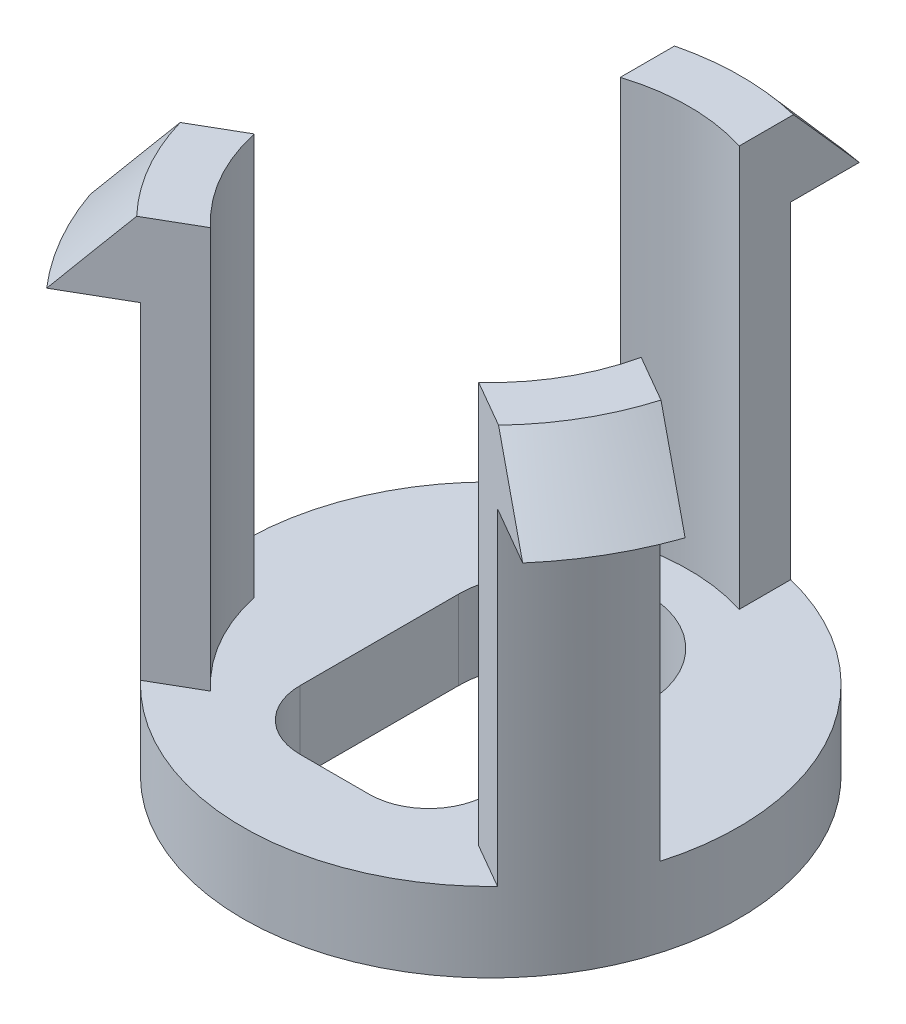
SolidWorks part; units mm, degrees
ref_plane "Front Plane" through (0, 0, 0) normal (0, 0, 1) x (1, 0, 0)
ref_plane "Top Plane" through (0, 0, 0) normal (0, 1, 0) x (1, 0, 0)
ref_plane "Right Plane" through (0, 0, 0) normal (1, 0, 0) x (0, 0, -1)
sketch "Sketch1" plane through (0, 0, 0) normal (0, 1, 0) x (1, 0, 0)
  circle A0 centre (0, 0) radius 5
  circle A1 centre (0, 0) radius 3.8 construction
  dimension "D1" = 10
  dimension "D2" = 1.2
extrude "Boss-Extrude1" add sketch "Sketch1" along normal blind 1.6
sketch "Sketch2" plane through (0, 1.6, 0) normal (0, 1, 0) x (1, 0, 0)
  line L2 (-1.2, 4.8539) -> (-1.2, 3.8158)
  line L4 (1.2, 4.8539) -> (1.2, 3.8158)
  circle A0 centre (0, 0) radius 5 construction
  arc A1 (1.2, 4.8539) -> (-1.2, 4.8539) centre (0, 0) ccw
  arc A2 (1.2, 3.8158) -> (-1.2, 3.8158) centre (0, 0) ccw
  circle A3 centre (0, 0) radius 5 construction
  circle A4 centre (0, 0) radius 4 construction
  dimension "D2" = 1.2
  dimension "D3" = 1.2
  dimension "D1" = 1
extrude "Boss-Extrude2" add sketch "Sketch2" along normal blind 8.1
pattern_circular "CirPattern3" count 3 over 360 about axis through (0, 0, 0) along (0, 1, 0) of "Boss-Extrude2"
sketch "Sketch3" plane through (0, 0, 0) normal (1, 0, 0) x (0, 0, -1)
  line L0 (5.0539, 9.7) -> (6.3539, 8.2)
  line L2 (6.3539, 8.2) -> (4.8539, 8.2)
  line L4 (4.8539, 9.7) -> (4.8539, 1.6) construction
  line L5 (4.8539, 8.2) -> (4.8539, 9.7)
  line L6 (4.8539, 9.7) -> (5.0539, 9.7)
  dimension "D1" = 1.5
  dimension "D2" = 1.5
  dimension "D3" = 0.2
sketch "Sketch6" plane through (0, 9.7, 0) normal (0, 1, 0) x (1, 0, 0)
  circle A0 centre (0, 0) radius 5
sweep "Sweep3" add profiles "Sketch3" path "Sketch6"
sketch "Sketch7" plane through (0, 1.6, 0) normal (0, 1, 0) x (1, 0, 0)
  line L0 (-3.9045, -0.8686) -> (-4.8036, -1.3877) construction
  line L1 (-3.9045, -0.8686) -> (-4.8036, -1.3877)
  line L2 (-1.2, 4.8539) -> (-1.2, 3.8158) construction
  line L3 (1.2, 3.8158) -> (1.2, 4.8539) construction
  line L4 (4.8036, -1.3877) -> (3.9045, -0.8686) construction
  line L5 (2.7045, -2.9471) -> (3.6036, -3.4662) construction
  line L6 (-3.6036, -3.4662) -> (-2.7045, -2.9471) construction
  line L7 (-1.2, 4.8539) -> (-1.2, 3.8158)
  line L8 (1.2, 3.8158) -> (1.2, 4.8539)
  line L9 (4.8036, -1.3877) -> (3.9045, -0.8686)
  line L10 (2.7045, -2.9471) -> (3.6036, -3.4662)
  line L11 (-3.6036, -3.4662) -> (-2.7045, -2.9471)
  arc A0 (-1.2, 4.8539) -> (-4.8036, -1.3877) centre (0, 0) ccw construction
  arc A1 (-1.2, 4.8539) -> (-4.8036, -1.3877) centre (0, 0) ccw
  arc A2 (4.8036, -1.3877) -> (1.2, 4.8539) centre (0, 0) ccw construction
  arc A3 (1.2, 3.8158) -> (-1.2, 3.8158) centre (0, 0) ccw construction
  arc A4 (-3.6036, -3.4662) -> (3.6036, -3.4662) centre (0, 0) ccw construction
  arc A5 (-3.9045, -0.8686) -> (-2.7045, -2.9471) centre (0, 0) ccw construction
  arc A6 (2.7045, -2.9471) -> (3.9045, -0.8686) centre (0, 0) ccw construction
  arc A7 (4.8036, -1.3877) -> (1.2, 4.8539) centre (0, 0) ccw
  arc A8 (1.2, 3.8158) -> (-1.2, 3.8158) centre (0, 0) ccw
  arc A9 (-3.6036, -3.4662) -> (3.6036, -3.4662) centre (0, 0) ccw
  arc A10 (-3.9045, -0.8686) -> (-2.7045, -2.9471) centre (0, 0) ccw
  arc A11 (2.7045, -2.9471) -> (3.9045, -0.8686) centre (0, 0) ccw
extrude "Cut-Extrude2" cut sketch "Sketch7" along normal through all
sketch "Sketch8" plane through (0, 8.2, 0) normal (0, -1, 0) x (1, 0, 0)
  line L0 (-3.6036, 3.4662) -> (-2.7045, 2.9471) construction
  line L1 (-3.6036, 3.4662) -> (-4.8036, 4.159)
  line L2 (-3.9045, 0.8686) -> (-4.8036, 1.3877) construction
  line L3 (-1.2, -4.8539) -> (-1.2, -3.8158) construction
  line L4 (1.2, -3.8158) -> (1.2, -4.8539) construction
  line L5 (4.8036, 1.3877) -> (3.9045, 0.8686) construction
  line L6 (2.7045, 2.9471) -> (3.6036, 3.4662) construction
  line L7 (-6.0036, 2.0805) -> (-4.8036, 1.3877)
  line L8 (-1.2, -4.8539) -> (-1.2, -6.2395)
  line L9 (1.2, -6.2395) -> (1.2, -4.8539)
  line L10 (4.8036, 1.3877) -> (6.0036, 2.0805)
  line L11 (4.8036, 4.159) -> (3.6036, 3.4662)
  circle A0 centre (0, 0) radius 6.3539 construction
  arc A1 (-6.0036, 2.0805) -> (-1.2, -6.2395) centre (0, 0) ccw
  arc A2 (3.6036, 3.4662) -> (-3.6036, 3.4662) centre (0, 0) ccw construction
  arc A3 (-4.8036, 1.3877) -> (-1.2, -4.8539) centre (0, 0) ccw
  arc A4 (1.2, -6.2395) -> (6.0036, 2.0805) centre (0, 0) ccw
  arc A5 (1.2, -4.8539) -> (4.8036, 1.3877) centre (0, 0) ccw
  arc A6 (3.6036, 3.4662) -> (-3.6036, 3.4662) centre (0, 0) ccw
  arc A7 (4.8036, 4.159) -> (-4.8036, 4.159) centre (0, 0) ccw
extrude "Cut-Extrude3" cut sketch "Sketch8" against normal through all
sketch "Sketch9" plane through (0, 1.6, 0) normal (0, 1, 0) x (1, 0, 0)
  line L0 (1.9, -3.15) -> (1.9, 1.25)
  line L1 (-1.9, -3.15) -> (1.9, -3.15)
  line L2 (-1.9, -3.15) -> (-1.9, 1.25)
  line L4 (-1.5, -2.75) -> (1.5, -2.75) construction
  line L5 (-1.5, -2.75) -> (-1.5, 1.25) construction
  line L7 (1.5, -2.75) -> (1.5, 1.25) construction
  line L8 (-1.5, -2.75) -> (1.5, 1.25) construction
  line L9 (-1.5, 1.25) -> (1.5, -2.75) construction
  arc A0 (-1.5, 1.25) -> (1.5, 1.25) centre (0, 1.25) cw construction
  arc A1 (-1.9, 1.25) -> (1.9, 1.25) centre (0, 1.25) cw
  point P0 (0, -0.75)
  dimension "D2" = 4
  dimension "D3" = 1.5
  dimension "D1" = 3
  dimension "D4" = 0.4
extrude "Cut-Extrude4" cut sketch "Sketch9" against normal through all
fillet "Fillet1" radius 1.2 2 edges at (1.9, 0.8, 3.15) (-1.9, 0.8, 3.15)
